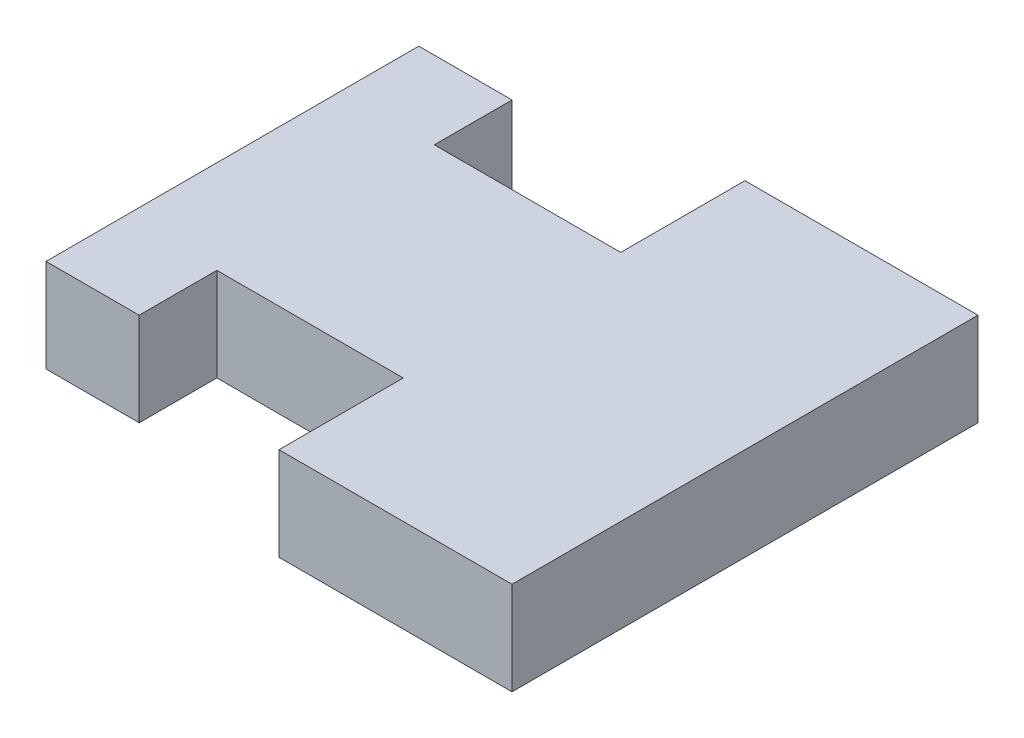
SolidWorks part; units mm, degrees
ref_plane "Front Plane" through (0, 0, 0) normal (0, 0, 1) x (1, 0, 0)
ref_plane "Top Plane" through (0, 0, 0) normal (0, 1, 0) x (1, 0, 0)
ref_plane "Right Plane" through (0, 0, 0) normal (1, 0, 0) x (0, 0, -1)
sketch "Sketch1" plane through (0, 0, 0) normal (0, 1, 0) x (1, 0, 0)
  line L1 (0, 1.5) -> (-0.75, 1.5)
  line L2 (-0.75, 1.5) -> (-0.75, 1.1)
  line L3 (-0.75, 1.1) -> (-1.35, 1.1)
  line L4 (-1.35, 1.1) -> (-1.35, 0.4) construction
  line L5 (-1.35, 0.4) -> (-0.75, 0.4)
  line L6 (-0.75, 0.4) -> (-0.75, 0)
  line L7 (-0.75, 0) -> (0, 0)
  line L8 (0, 1.5) -> (0, 0)
  line L9 (-1.35, 0.4) -> (-1.35, 0.15)
  line L10 (-1.35, 0.15) -> (-1.65, 0.15)
  line L11 (-1.65, 0.15) -> (-1.65, 1.35)
  line L12 (-1.65, 1.35) -> (-1.35, 1.35)
  line L13 (-1.35, 1.35) -> (-1.35, 1.1)
  point P3 (-1.35, 0.75)
  point P10 (0, 0.75)
  point P11 (-1.65, 0.75)
  dimension "D1" = 0.75
  dimension "D2" = 1.5
  dimension "D3" = 0.7
  dimension "D4" = 0.6
  dimension "D5" = 0.3
  dimension "D6" = 1.2
extrude "Boss-Extrude1" add sketch "Sketch1" along normal blind 0.3
equation "\"t\"= 0.3'thickness of the sheets"
equation "\"FlexJoint\"= 0.15'Width of flextures"
equation "\"FoldJoint\"= 0.4'Width of folding joints"
equation "\"AssembleAngle\"= 90'Angle of assembly parts"
equation "\"D1@Boss-Extrude1\"=\"t\""
